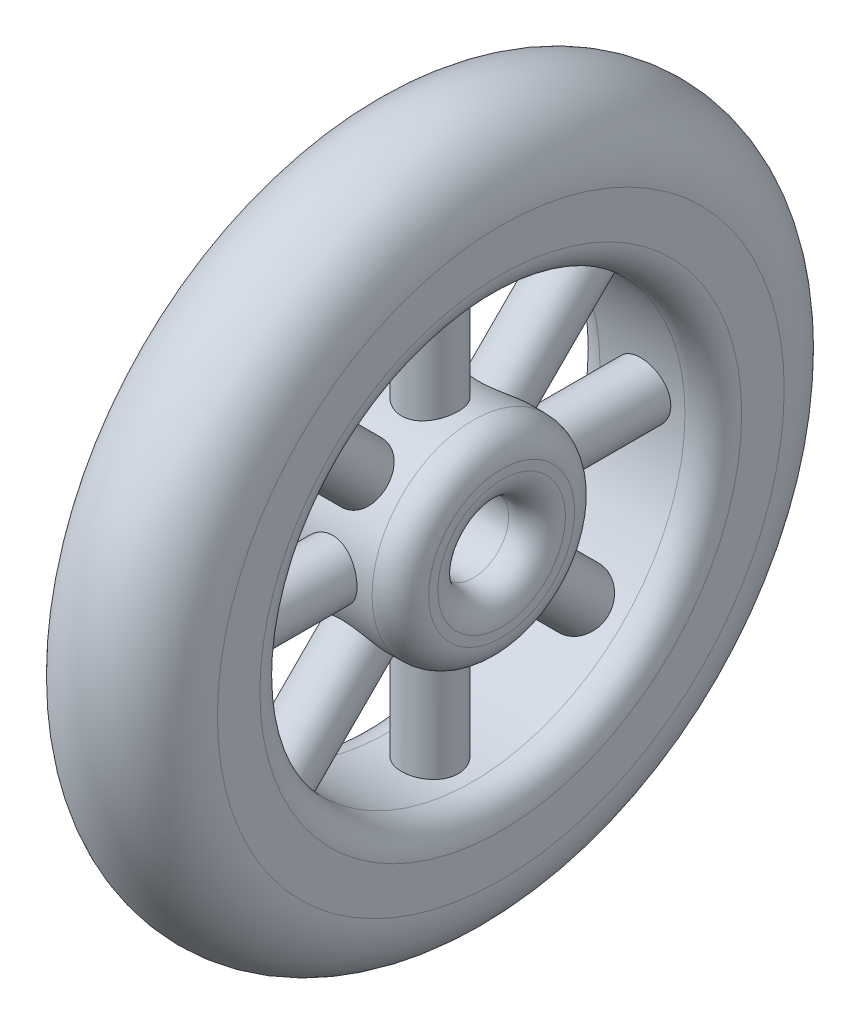
SolidWorks part; units mm, degrees
material "ABS"
ref_plane "Front Plane" through (0, 0, 0) normal (0, 0, 1) x (1, 0, 0)
ref_plane "Top Plane" through (0, 0, 0) normal (0, 1, 0) x (1, 0, 0)
ref_plane "Right Plane" through (0, 0, 0) normal (1, 0, 0) x (0, 0, -1)
sketch "Sketch3" plane through (0, 0, 0) normal (0, 0, 1) x (1, 0, 0)
  line L2 (13.3734, 0) -> (-13.3734, 0) construction
  line L4 (0, 1.5875) -> (0, 15.875) construction
  line L5 (-1.9422, 1.5875) -> (1.9422, 1.5875)
  line L6 (1.9422, 4.5382) -> (-1.9422, 4.5382)
  line L7 (0, -8.7312) -> (0, 8.7312) construction
  line L8 (-11.9772, 0) -> (12.3381, 0) construction
  line L11 (3.2122, 2.8575) -> (3.2122, 3.2682)
  line L13 (-3.2122, 2.8575) -> (-3.2122, 3.2682)
  line L14 (-3.175, 12.7) -> (-3.175, 10.795)
  line L15 (-1.905, 9.525) -> (1.905, 9.525)
  line L16 (3.175, 10.795) -> (3.175, 12.7)
  arc A0 (3.175, 12.7) -> (-3.175, 12.7) centre (0, 12.7) ccw
  arc A1 (1.905, 9.525) -> (3.175, 10.795) centre (1.905, 10.795) ccw
  arc A2 (-1.905, 9.525) -> (-3.175, 10.795) centre (-1.905, 10.795) cw
  arc A3 (-3.2122, 2.8575) -> (-1.9422, 1.5875) centre (-1.9422, 2.8575) ccw
  arc A4 (-3.2122, 3.2682) -> (-1.9422, 4.5382) centre (-1.9422, 3.2682) cw
  arc A5 (3.2122, 2.8575) -> (1.9422, 1.5875) centre (1.9422, 2.8575) cw
  arc A6 (3.2122, 3.2682) -> (1.9422, 4.5382) centre (1.9422, 3.2682) ccw
  dimension "D1" = 6.35
  dimension "D2" = 1.27
  dimension "D3" = 1.27
  dimension "D4" = 3.2122
  dimension "D5" = 1.5875
  dimension "D6" = 4.5382
  dimension "D7" = 15.875
revolve "Revolve1" add sketch "Sketch3" angle 360 about L8
sketch "Sketch5" plane through (0, 0, 0) normal (1, 0, 0) x (0, 0, -1)
  line L0 (0, 3.0628) -> (0, 12.7)
  line L1 (0, 2.8575) -> (0, 3.2682) construction
sweep "Sweep1" add path "Sketch5" circular profile diameter 2.54 parameters "D3"=2.54
pattern_circular "CirPattern1" count 8 over 360 about axis through (-11.9772, 0, 0) along (1, 0, 0) of "Sweep1"
